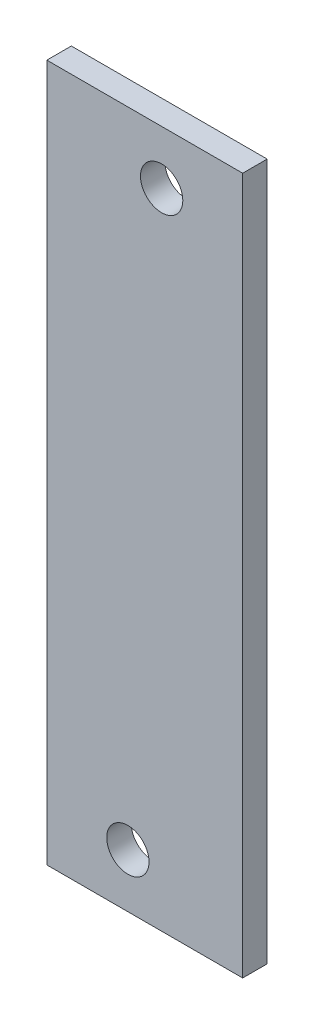
SolidWorks part; units mm, degrees
material "Custom Plastic"
ref_plane "X-Y Datum" through (0, 0, 0) normal (0, 0, 1) x (1, 0, 0)
ref_plane "X-Z Datum" through (0, 0, 0) normal (0, 1, 0) x (1, 0, 0)
ref_plane "Y-Z Datum" through (0, 0, 0) normal (1, 0, 0) x (0, 0, -1)
sketch "Sketch1" plane through (0, 0, 0) normal (0, 0, 1) x (1, 0, 0)
  line L0 (0, 42.164) -> (0, -42.164) construction
  line L1 (-14, 49.83) -> (14, 49.83)
  line L2 (-14, 49.83) -> (-14, -49.83)
  line L3 (-14, -49.83) -> (14, -49.83)
  line L4 (14, 49.83) -> (14, -49.83)
  line L5 (-14, 49.83) -> (14, -49.83) construction
  line L6 (-14, -49.83) -> (14, 49.83) construction
  line L7 (-2.413, -42.164) -> (2.413, -42.164) construction
  line L8 (-2.413, 42.164) -> (2.413, 42.164) construction
  circle A0 centre (-2.413, -42.164) radius 3.025
  circle A1 centre (2.413, 42.164) radius 3.025
  point P0 (0, 0)
  point P9 (0, 0)
  point P12 (0, -42.164)
  point P14 (0, 42.164)
  point P16 (-2.413, -42.164)
  point P17 (2.413, 42.164)
  dimension "D5" = 6.05
  dimension "D1" = 28
  dimension "D2" = 99.66
  dimension "D3" = 84.328
  dimension "D4" = 4.826
extrude "Boss-Extrude1" add sketch "Sketch1" along normal blind 3.5
